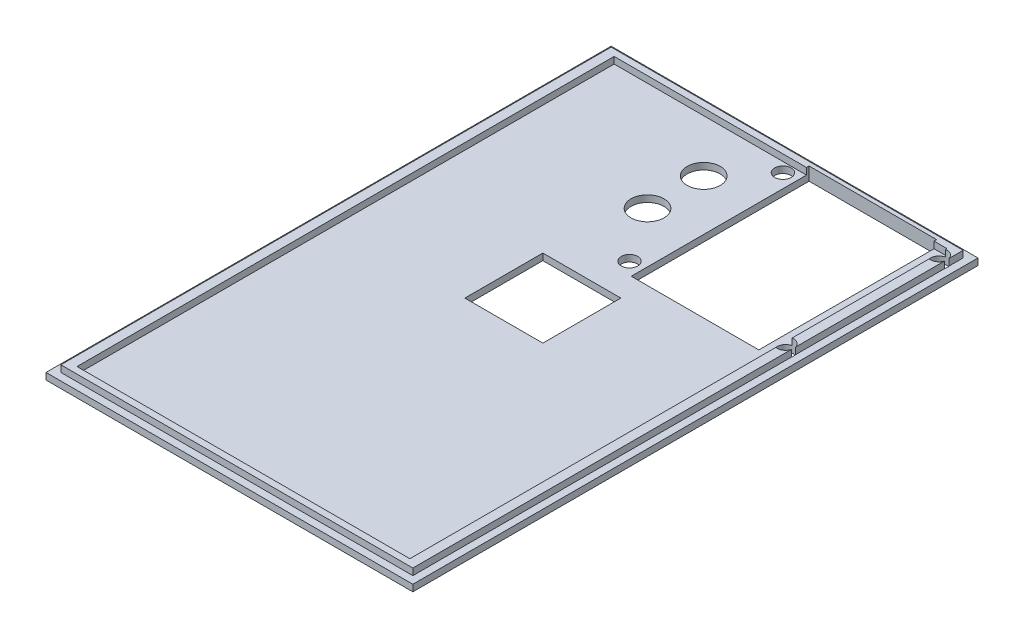
SolidWorks part; units mm, degrees
ref_plane "Front Plane" through (0, 0, 0) normal (0, 0, 1) x (1, 0, 0)
ref_plane "Top Plane" through (0, 0, 0) normal (0, 1, 0) x (1, 0, 0)
ref_plane "Right Plane" through (0, 0, 0) normal (1, 0, 0) x (0, 0, -1)
sketch "Sketch1" plane through (0, 0, 0) normal (0, 1, 0) x (1, 0, 0)
  line L1 (-27.75, -42.75) -> (27.75, -42.75)
  line L2 (-27.75, -42.75) -> (-27.75, 42.75)
  line L3 (-27.75, 42.75) -> (27.75, 42.75)
  line L4 (27.75, -42.75) -> (27.75, 42.75)
  line L5 (-27.75, -42.75) -> (27.75, 42.75) construction
  line L6 (-27.75, 42.75) -> (27.75, -42.75) construction
  point P0 (0, 0)
  dimension "D1" = 85.5
  dimension "D2" = 55.5
extrude "Boss-Extrude1" add sketch "Sketch1" along normal blind 1
sketch "Sketch2" plane through (0, 1, 0) normal (0, 1, 0) x (1, 0, 0)
  line L1 (-26.625, -41.625) -> (26.625, -41.625)
  line L2 (-26.625, -41.625) -> (-26.625, 41.625)
  line L3 (-26.625, 41.625) -> (26.625, 41.625)
  line L4 (26.625, -41.625) -> (26.625, 41.625)
  line L5 (-26.625, -41.625) -> (26.625, 41.625) construction
  line L6 (-26.625, 41.625) -> (26.625, -41.625) construction
  line L7 (-25.1779, -40.6301) -> (25.1779, -40.6301)
  line L8 (-25.1779, -40.6301) -> (-25.1779, 40.6301)
  line L9 (-25.1779, 40.6301) -> (25.1779, 40.6301)
  line L10 (25.1779, -40.6301) -> (25.1779, 40.6301)
  line L11 (-25.1779, -40.6301) -> (25.1779, 40.6301) construction
  line L12 (-25.1779, 40.6301) -> (25.1779, -40.6301) construction
  point P0 (0, 0)
  point P6 (0, 0)
  dimension "D1" = 53.25
  dimension "D2" = 83.25
extrude "Boss-Extrude2" add sketch "Sketch2" along normal blind 1
sketch "Sketch3" plane through (0, 0, 0) normal (0, -1, 0) x (1, 0, 0)
  line L0 (27.75, -42.75) -> (-27.75, -42.75) construction
  line L1 (-27.75, -42.75) -> (-27.75, 42.75) construction
  line L3 (3.919, -41.0247) -> (23.219, -41.0247)
  line L4 (3.919, -41.0247) -> (3.919, -14.1247)
  line L5 (3.919, -14.1247) -> (23.219, -14.1247)
  line L6 (23.219, -41.0247) -> (23.219, -14.1247)
  line L7 (3.919, -41.0247) -> (23.219, -14.1247) construction
  line L8 (3.919, -14.1247) -> (23.219, -41.0247) construction
  line L9 (5.9913, 1.3242) -> (-5.8087, 1.3242)
  line L10 (5.9913, 1.3242) -> (5.9913, -10.4758)
  line L11 (5.9913, -10.4758) -> (-5.8087, -10.4758)
  line L12 (-5.8087, 1.3242) -> (-5.8087, -10.4758)
  line L13 (5.9913, 1.3242) -> (-5.8087, -10.4758) construction
  line L14 (5.9913, -10.4758) -> (-5.8087, 1.3242) construction
  circle A0 centre (-3.75, -32.75) radius 2.5
  circle A1 centre (-3.75, -24.25) radius 2.5
  circle A2 centre (1.819, -15.9624) radius 1.25
  circle A3 centre (25.419, -15.9631) radius 1.2488
  circle A4 centre (1.8186, -39.1624) radius 1.25
  circle A5 centre (25.419, -39.1624) radius 1.252
  point P8 (13.569, -27.5747)
  point P19 (0.0913, -4.5758)
  dimension "D1" = 10
  dimension "D3" = 8.5
  dimension "D6" = 21.4
  dimension "D8" = 23.2
  dimension "D2" = 24
  dimension "D4" = 19.3
  dimension "D5" = 26.9
  dimension "D7" = 23.6
  dimension "D9" = 11.8
  dimension "D10" = 11.8
extrude "Cut-Extrude2" cut sketch "Sketch3" against normal blind 3
